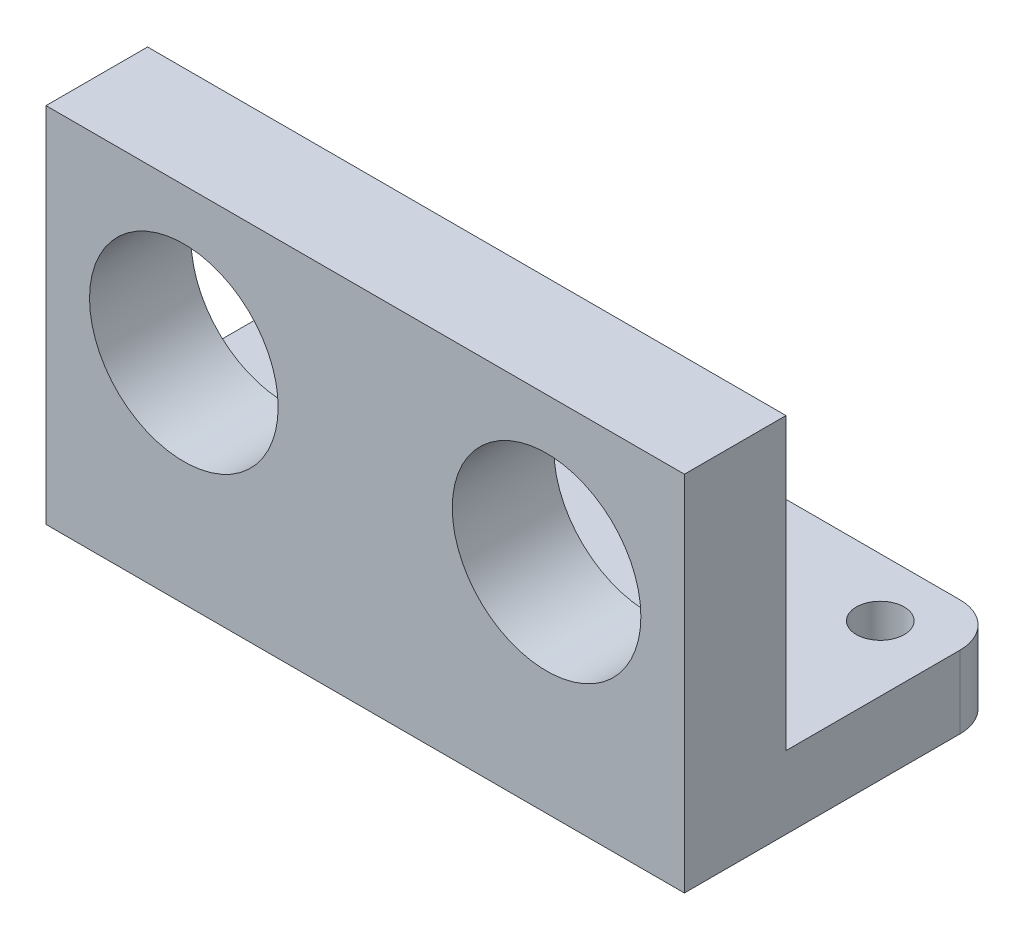
SolidWorks part; units mm, degrees
ref_plane "Front Plane" through (0, 0, 0) normal (0, 0, 1) x (1, 0, 0)
ref_plane "Top Plane" through (0, 0, 0) normal (0, 1, 0) x (1, 0, 0)
ref_plane "Right Plane" through (0, 0, 0) normal (1, 0, 0) x (0, 0, -1)
sketch "Sketch1" plane through (0, 0, 0) normal (0, 0, 1) x (1, 0, 0)
  line L0 (-316.175, 0) -> (15492.5733, 0) construction
  line L1 (22, 10) -> (-22, 10)
  line L2 (22, 10) -> (22, -10)
  line L4 (-22, 10) -> (-22, -10)
  line L5 (22, 10) -> (-22, -10) construction
  line L6 (22, -10) -> (-22, 10) construction
  line L7 (-22, -10) -> (-22, -15)
  line L8 (-22, -15) -> (22, -15)
  line L9 (22, -15) -> (22, -10)
  circle A0 centre (-12.5, 0) radius 6.5
  circle A1 centre (12.5, 0) radius 6.5
  point P0 (0, 0)
  dimension "D1" = 13
  dimension "D5" = 10
  dimension "D2" = 25
  dimension "D3" = 44
  dimension "D4" = 12.5
  dimension "D6" = 25
extrude "Boss-Extrude1" add sketch "Sketch1" along normal blind 7
sketch "Sketch2" plane through (0, 0, 0) normal (0, 0, -1) x (-1, 0, 0)
  line L0 (0, -1000) -> (0, 49000) construction
  line L1 (-22, -15) -> (22, -15)
  line L2 (-22, -15) -> (-22, -10)
  line L3 (-22, -10) -> (22, -10)
  line L4 (-22, -15) -> (22, -15)
  line L5 (22, -15) -> (22, 10)
  line L6 (22, 10) -> (-22, 10)
  line L7 (-22, 10) -> (-22, -15)
  line L8 (-22, -15) -> (22, -15)
  line L9 (22, -15) -> (22, 10)
  line L10 (22, 10) -> (-22, 10)
  line L11 (-22, 10) -> (-22, -15)
  line L12 (22, -15) -> (22, -10)
  line M9 (-22, -15) -> (22, -15)
  line M10 (22, -15) -> (22, 10)
  line M12 (-22, 10) -> (-22, -15)
  dimension "D2" = 5
  dimension "D1" = 0
extrude "Boss-Extrude2" add sketch "Sketch2" along normal blind 15 contours L0 L3 M9 M12 | L0 L8 L3 M10
sketch "Sketch3" plane through (0, -10, 0) normal (0, 1, 0) x (1, 0, 0)
  line L0 (22, 0) -> (-22, 0) construction
  line L1 (-22, 0) -> (-22, -7) construction
  line L2 (-22, -7) -> (22, -7) construction
  line L3 (22, -7) -> (22, 0) construction
  line L4 (-22, 0) -> (22, 0) construction
  line L5 (22, 0) -> (22, 15) construction
  line L6 (22, 15) -> (-22, 15) construction
  line L7 (-22, 15) -> (-22, 0) construction
  line L8 (22, 0) -> (-22, 0)
  line L9 (-22, 0) -> (-22, -7)
  line L10 (-22, -7) -> (22, -7)
  line L11 (22, -7) -> (22, 0)
  line L12 (-22, 0) -> (22, 0)
  line L13 (22, 0) -> (22, 15)
  line L14 (22, 15) -> (-22, 15)
  line L15 (-22, 15) -> (-22, 0)
  line L16 (-1003.8003, 11) -> (48996.1997, 11) construction
  line L17 (0, -1000) -> (0, 49000) construction
  circle A0 centre (-17.5, 11) radius 1.651
  circle A1 centre (0, 11) radius 1.651
  circle A2 centre (17.5, 11) radius 1.651
  point P17 (0, 0)
  dimension "D1" = 3.302
  dimension "D2" = 35
  dimension "D3" = 11
extrude "Cut-Extrude1" cut sketch "Sketch3" against normal through all contours A2 | A1 | A0
fillet "Fillet1" radius 3 2 edges at (-22, -12.5, -15) (22, -12.5, -15)
